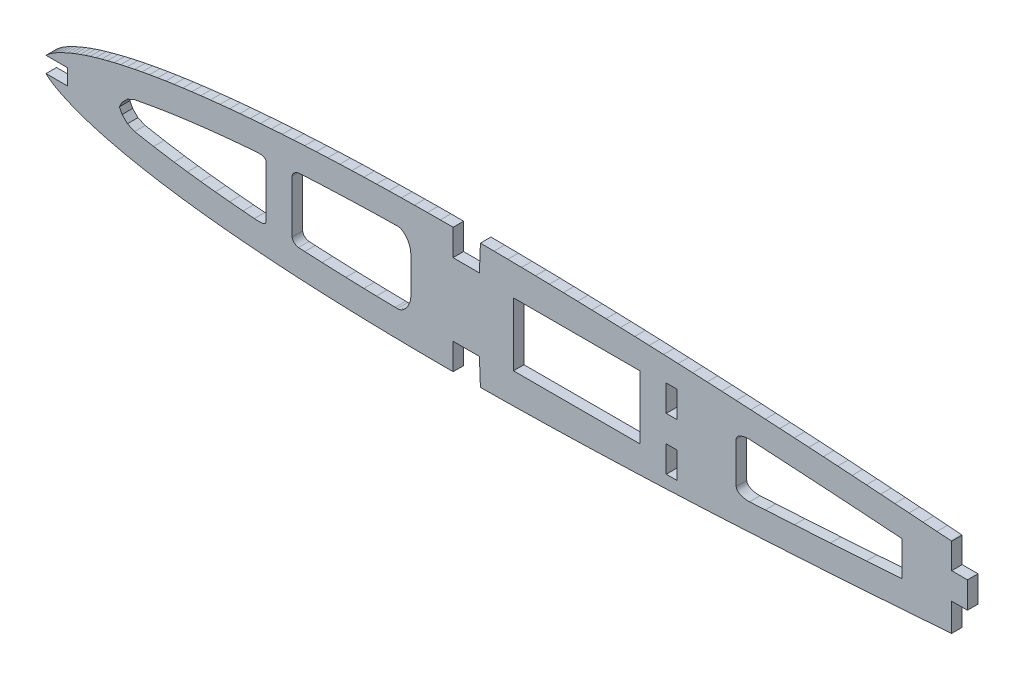
SolidWorks part; units mm, degrees
ref_plane "前视基准面" through (0, 0, 0) normal (0, 0, 1) x (1, 0, 0)
ref_plane "上视基准面" through (0, 0, 0) normal (0, 1, 0) x (1, 0, 0)
ref_plane "右视基准面" through (0, 0, 0) normal (1, 0, 0) x (0, 0, -1)
sketch "Model" plane through (0, 0, 0) normal (0, 0, 1) x (1, 0, 0)
  line L0 (334.1432, -155.4428) -> (338.2569, -155.4428)
  line L1 (338.2569, -155.4428) -> (338.2569, -158.4428)
  line L2 (338.2569, -158.4428) -> (334.1432, -158.4428)
  line L3 (416.4039, -150.0848) -> (416.5959, -145.0858)
  line L4 (416.4039, -150.0848) -> (411.4039, -150.0688)
  line L5 (411.4039, -150.0688) -> (411.4209, -145.0688)
  line L6 (416.4039, -163.8008) -> (416.5959, -168.7998)
  line L7 (416.4039, -163.8008) -> (411.4039, -163.8178)
  line L8 (411.4039, -163.8178) -> (411.4209, -168.8178)
  line L9 (506.0395, -149.3593) -> (505.9039, -149.3488)
  line L10 (505.9039, -149.3488) -> (503.2519, -149.1468)
  line L11 (503.2519, -149.1468) -> (500.5999, -148.9498)
  line L12 (500.5999, -148.9498) -> (497.9479, -148.7548)
  line L13 (497.9479, -148.7548) -> (495.2519, -148.5618)
  line L14 (495.2519, -148.5618) -> (492.5569, -148.3718)
  line L15 (492.5569, -148.3718) -> (489.8609, -148.1858)
  line L16 (489.8609, -148.1858) -> (487.1329, -147.9998)
  line L17 (487.1329, -147.9998) -> (484.4059, -147.8178)
  line L18 (484.4059, -147.8178) -> (481.6779, -147.6418)
  line L19 (481.6779, -147.6418) -> (478.9279, -147.4708)
  line L20 (478.9279, -147.4708) -> (476.1779, -147.3038)
  line L21 (476.1779, -147.3038) -> (473.4269, -147.1408)
  line L22 (473.4269, -147.1408) -> (470.6669, -146.9798)
  line L23 (470.6669, -146.9798) -> (467.9079, -146.8218)
  line L24 (467.9079, -146.8218) -> (465.1469, -146.6688)
  line L25 (465.1469, -146.6688) -> (462.3869, -146.5218)
  line L26 (462.3869, -146.5218) -> (459.6279, -146.3828)
  line L27 (459.6279, -146.3828) -> (456.8669, -146.2488)
  line L28 (456.8669, -146.2488) -> (454.1169, -146.1228)
  line L29 (454.1169, -146.1228) -> (451.3669, -146.0028)
  line L30 (451.3669, -146.0028) -> (448.6159, -145.8878)
  line L31 (448.6159, -145.8878) -> (445.8879, -145.7798)
  line L32 (445.8879, -145.7798) -> (443.1609, -145.6788)
  line L33 (443.1609, -145.6788) -> (440.4329, -145.5848)
  line L34 (440.4329, -145.5848) -> (437.7379, -145.4978)
  line L35 (437.7379, -145.4978) -> (435.0419, -145.4188)
  line L36 (435.0419, -145.4188) -> (432.3459, -145.3468)
  line L37 (432.3459, -145.3468) -> (429.6939, -145.2828)
  line L38 (429.6939, -145.2828) -> (427.0429, -145.2268)
  line L39 (427.0429, -145.2268) -> (424.3899, -145.1788)
  line L40 (424.3899, -145.1788) -> (421.7919, -145.1388)
  line L41 (421.7919, -145.1388) -> (419.1939, -145.1078)
  line L42 (419.1939, -145.1078) -> (416.5959, -145.0858)
  line L43 (350.9749, -154.3268) -> (354.5644, -153.6678)
  line L44 (354.5644, -153.6678) -> (358.4449, -153.0538)
  line L45 (358.4449, -153.0538) -> (360.9819, -152.7033)
  line L46 (360.9819, -152.7033) -> (363.5229, -152.3838)
  line L47 (363.5229, -152.3838) -> (366.2624, -152.0758)
  line L48 (366.2624, -152.0758) -> (369.0039, -151.7948)
  line L49 (369.0039, -151.7948) -> (371.5529, -151.5622)
  line L50 (371.5529, -151.5622) -> (373.8859, -151.3668)
  line L51 (382.21, -150.8083) -> (383.2599, -150.7478)
  line L52 (383.2599, -150.7478) -> (386.5334, -150.5888)
  line L53 (386.5334, -150.5888) -> (386.6385, -150.5846)
  line L54 (386.6385, -150.5846) -> (391.0509, -150.4073)
  line L55 (391.0509, -150.4073) -> (394.4779, -150.2968)
  line L56 (394.4779, -150.2968) -> (396.8539, -150.2348)
  line L57 (396.8539, -150.2348) -> (400.4194, -150.1623)
  line L58 (400.4194, -150.1623) -> (400.8605, -150.1557)
  line L59 (400.8351, -163.7295) -> (400.4194, -163.7233)
  line L60 (400.4194, -163.7233) -> (396.8539, -163.6508)
  line L61 (396.8539, -163.6508) -> (394.4779, -163.5888)
  line L62 (394.4779, -163.5888) -> (391.0509, -163.4783)
  line L63 (391.0509, -163.4783) -> (386.5334, -163.2968)
  line L64 (386.5334, -163.2968) -> (383.2599, -163.1378)
  line L65 (383.2599, -163.1378) -> (382.0634, -163.0689)
  line L66 (373.6903, -162.5024) -> (371.5529, -162.3235)
  line L67 (371.5529, -162.3235) -> (369.0039, -162.0908)
  line L68 (369.0039, -162.0908) -> (366.2624, -161.8098)
  line L69 (366.2624, -161.8098) -> (363.5229, -161.5018)
  line L70 (363.5229, -161.5018) -> (360.9819, -161.1823)
  line L71 (360.9819, -161.1823) -> (358.4449, -160.8318)
  line L72 (358.4449, -160.8318) -> (354.5644, -160.2178)
  line L73 (354.5644, -160.2178) -> (350.9749, -159.5588)
  line L74 (350.9749, -154.3268) -> (349.5928, -154.917)
  line L75 (349.5928, -154.917) -> (348.5947, -155.9412)
  line L76 (348.5947, -155.9412) -> (348.068, -156.9428)
  line L77 (350.9749, -159.5588) -> (349.5928, -158.9686)
  line L78 (349.5928, -158.9686) -> (348.5947, -157.9444)
  line L79 (348.5947, -157.9444) -> (348.068, -156.9428)
  line L80 (467.6693, -151.8109) -> (470.6669, -151.9798)
  line L81 (470.6669, -151.9798) -> (477.1529, -152.3643)
  line L82 (477.1529, -152.3643) -> (483.0419, -152.7298)
  line L83 (483.0419, -152.7298) -> (489.8609, -153.1858)
  line L84 (489.8609, -153.1858) -> (496.5999, -153.6583)
  line L85 (496.5999, -153.6583) -> (496.5999, -160.2273)
  line L86 (496.5999, -160.2273) -> (489.8609, -160.6998)
  line L87 (489.8609, -160.6998) -> (483.0419, -161.1558)
  line L88 (483.0419, -161.1558) -> (476.1779, -161.5818)
  line L89 (476.1779, -161.5818) -> (470.6669, -161.9058)
  line L90 (470.6669, -161.9058) -> (467.6693, -162.0747)
  line L91 (403.377, -153.3609) -> (403.377, -160.5247)
  line L92 (465.1469, -153.0708) -> (465.1469, -160.8149)
  line L93 (380.8691, -151.9428) -> (380.8691, -161.9428)
  line L94 (375.8691, -161.9428) -> (375.8691, -151.9428)
  line L96 (451.8649, -150.4428) -> (453.8649, -150.4428)
  line L97 (453.8649, -150.4428) -> (453.8649, -155.4428)
  line L98 (453.8649, -155.4428) -> (451.8649, -155.4428)
  line L99 (451.8649, -160.4428) -> (453.8649, -160.4428)
  line L100 (453.8649, -160.4428) -> (453.8649, -165.4428)
  line L101 (453.8649, -165.4428) -> (451.8649, -165.4428)
  line L102 (451.8649, -150.4428) -> (451.8649, -155.4428)
  line L103 (451.8649, -160.4428) -> (451.8649, -165.4428)
  line L104 (446.8649, -150.9428) -> (446.8649, -162.9428)
  line L105 (446.8649, -162.9428) -> (422.8649, -162.9428)
  line L106 (422.8649, -162.9428) -> (422.8649, -150.9428)
  line L107 (422.8649, -150.9428) -> (446.8649, -150.9428)
  line L108 (509.0395, -156.7128) -> (509.0395, -159.2128)
  line L109 (509.0395, -156.7128) -> (509.0395, -154.2128)
  line L110 (509.0395, -154.2128) -> (506.0395, -154.2128)
  line L111 (509.0395, -159.2128) -> (506.0395, -159.2128)
  line L112 (506.0395, -154.2128) -> (506.0395, -149.3593)
  line L113 (506.0395, -159.2128) -> (506.0395, -164.5264)
  line L114 (411.4209, -145.0688) -> (408.9909, -145.0728)
  line L115 (408.9909, -145.0728) -> (406.5289, -145.0858)
  line L116 (406.5289, -145.0858) -> (404.0689, -145.1088)
  line L117 (404.0689, -145.1088) -> (401.6079, -145.1418)
  line L118 (401.6079, -145.1418) -> (399.2309, -145.1828)
  line L119 (399.2309, -145.1828) -> (396.8539, -145.2348)
  line L120 (396.8539, -145.2348) -> (394.4779, -145.2968)
  line L121 (394.4779, -145.2968) -> (392.1929, -145.3668)
  line L122 (392.1929, -145.3668) -> (389.9089, -145.4478)
  line L123 (389.9089, -145.4478) -> (387.6249, -145.5398)
  line L124 (387.6249, -145.5398) -> (385.4419, -145.6378)
  line L125 (385.4419, -145.6378) -> (383.2599, -145.7478)
  line L126 (383.2599, -145.7478) -> (381.0779, -145.8698)
  line L127 (381.0779, -145.8698) -> (379.0049, -145.9968)
  line L128 (379.0049, -145.9968) -> (376.9339, -146.1368)
  line L129 (376.9339, -146.1368) -> (374.8629, -146.2888)
  line L130 (374.8629, -146.2888) -> (372.9089, -146.4448)
  line L131 (372.9089, -146.4448) -> (370.9559, -146.6138)
  line L132 (370.9559, -146.6138) -> (369.0039, -146.7948)
  line L133 (369.0039, -146.7948) -> (367.1759, -146.9778)
  line L134 (367.1759, -146.9778) -> (365.3489, -147.1738)
  line L135 (365.3489, -147.1738) -> (363.5229, -147.3838)
  line L136 (363.5229, -147.3838) -> (361.8279, -147.5918)
  line L137 (361.8279, -147.5918) -> (360.1359, -147.8148)
  line L138 (360.1359, -147.8148) -> (358.4449, -148.0538)
  line L139 (358.4449, -148.0538) -> (356.8909, -148.2868)
  line L140 (356.8909, -148.2868) -> (355.3389, -148.5358)
  line L141 (355.3389, -148.5358) -> (353.7899, -148.7998)
  line L142 (353.7899, -148.7998) -> (352.3799, -149.0558)
  line L143 (352.3799, -149.0558) -> (350.9749, -149.3268)
  line L144 (350.9749, -149.3268) -> (349.5719, -149.6148)
  line L145 (349.5719, -149.6148) -> (348.3139, -149.8908)
  line L146 (348.3139, -149.8908) -> (347.0599, -150.1828)
  line L147 (347.0599, -150.1828) -> (345.8099, -150.4938)
  line L148 (345.8099, -150.4938) -> (344.7079, -150.7838)
  line L149 (344.7079, -150.7838) -> (343.6099, -151.0918)
  line L150 (343.6099, -151.0918) -> (342.5179, -151.4198)
  line L151 (342.5179, -151.4198) -> (341.5759, -151.7218)
  line L152 (341.5759, -151.7218) -> (340.6399, -152.0448)
  line L153 (340.6399, -152.0448) -> (339.7119, -152.3898)
  line L154 (339.7119, -152.3898) -> (338.9339, -152.7018)
  line L155 (338.9339, -152.7018) -> (338.1629, -153.0328)
  line L156 (338.1629, -153.0328) -> (337.4009, -153.3818)
  line L157 (337.4009, -153.3818) -> (336.7869, -153.6818)
  line L158 (336.7869, -153.6818) -> (336.1839, -154.0018)
  line L159 (336.1839, -154.0018) -> (335.5939, -154.3478)
  line L160 (335.5939, -154.3478) -> (335.1439, -154.6418)
  line L161 (335.1439, -154.6418) -> (334.7099, -154.9578)
  line L162 (334.7099, -154.9578) -> (334.2959, -155.2998)
  line L163 (334.2959, -155.2998) -> (334.1432, -155.4428)
  line L164 (416.5959, -168.7998) -> (419.1939, -168.7778)
  line L165 (419.1939, -168.7778) -> (421.7919, -168.7468)
  line L166 (421.7919, -168.7468) -> (424.3899, -168.7078)
  line L167 (424.3899, -168.7078) -> (427.0429, -168.6588)
  line L168 (427.0429, -168.6588) -> (429.6939, -168.6028)
  line L169 (429.6939, -168.6028) -> (432.3459, -168.5388)
  line L170 (432.3459, -168.5388) -> (435.0419, -168.4668)
  line L171 (435.0419, -168.4668) -> (437.7379, -168.3878)
  line L172 (437.7379, -168.3878) -> (440.4329, -168.3008)
  line L173 (440.4329, -168.3008) -> (443.1609, -168.2068)
  line L174 (443.1609, -168.2068) -> (445.8879, -168.1058)
  line L175 (445.8879, -168.1058) -> (448.6159, -167.9978)
  line L176 (448.6159, -167.9978) -> (451.3669, -167.8838)
  line L177 (451.3669, -167.8838) -> (454.1169, -167.7628)
  line L178 (454.1169, -167.7628) -> (456.8669, -167.6368)
  line L179 (456.8669, -167.6368) -> (459.6279, -167.5028)
  line L180 (459.6279, -167.5028) -> (462.3869, -167.3638)
  line L181 (462.3869, -167.3638) -> (465.1469, -167.2168)
  line L182 (465.1469, -167.2168) -> (467.9079, -167.0638)
  line L183 (467.9079, -167.0638) -> (470.6669, -166.9068)
  line L184 (470.6669, -166.9068) -> (473.4269, -166.7448)
  line L185 (473.4269, -166.7448) -> (476.1779, -166.5818)
  line L186 (476.1779, -166.5818) -> (478.9279, -166.4158)
  line L187 (478.9279, -166.4158) -> (481.6779, -166.2438)
  line L188 (481.6779, -166.2438) -> (484.4059, -166.0678)
  line L189 (484.4059, -166.0678) -> (487.1329, -165.8858)
  line L190 (487.1329, -165.8858) -> (489.8609, -165.7008)
  line L191 (489.8609, -165.7008) -> (492.5569, -165.5138)
  line L192 (492.5569, -165.5138) -> (495.2519, -165.3238)
  line L193 (495.2519, -165.3238) -> (497.9479, -165.1308)
  line L194 (497.9479, -165.1308) -> (500.5999, -164.9368)
  line L195 (500.5999, -164.9368) -> (503.2519, -164.7388)
  line L196 (503.2519, -164.7388) -> (505.9039, -164.5368)
  line L197 (505.9039, -164.5368) -> (506.0395, -164.5264)
  line L198 (334.1432, -158.4428) -> (334.2959, -158.5858)
  line L199 (334.2959, -158.5858) -> (334.7099, -158.9278)
  line L200 (334.7099, -158.9278) -> (335.1439, -159.2438)
  line L201 (335.1439, -159.2438) -> (335.5939, -159.5388)
  line L202 (335.5939, -159.5388) -> (336.1839, -159.8848)
  line L203 (336.1839, -159.8848) -> (336.7869, -160.2038)
  line L204 (336.7869, -160.2038) -> (337.4009, -160.5038)
  line L205 (337.4009, -160.5038) -> (338.1629, -160.8538)
  line L206 (338.1629, -160.8538) -> (338.9339, -161.1838)
  line L207 (338.9339, -161.1838) -> (339.7119, -161.4958)
  line L208 (339.7119, -161.4958) -> (340.6399, -161.8408)
  line L209 (340.6399, -161.8408) -> (341.5759, -162.1638)
  line L210 (341.5759, -162.1638) -> (342.5179, -162.4668)
  line L211 (342.5179, -162.4668) -> (343.6099, -162.7938)
  line L212 (343.6099, -162.7938) -> (344.7079, -163.1018)
  line L213 (344.7079, -163.1018) -> (345.8099, -163.3928)
  line L214 (345.8099, -163.3928) -> (347.0599, -163.7028)
  line L215 (347.0599, -163.7028) -> (348.3139, -163.9948)
  line L216 (348.3139, -163.9948) -> (349.5719, -164.2708)
  line L217 (349.5719, -164.2708) -> (350.9749, -164.5598)
  line L218 (350.9749, -164.5598) -> (352.3799, -164.8308)
  line L219 (352.3799, -164.8308) -> (353.7899, -165.0858)
  line L220 (353.7899, -165.0858) -> (355.3389, -165.3498)
  line L221 (355.3389, -165.3498) -> (356.8909, -165.5988)
  line L222 (356.8909, -165.5988) -> (358.4449, -165.8318)
  line L223 (358.4449, -165.8318) -> (360.1359, -166.0708)
  line L224 (360.1359, -166.0708) -> (361.8279, -166.2938)
  line L225 (361.8279, -166.2938) -> (363.5229, -166.5018)
  line L226 (363.5229, -166.5018) -> (365.3489, -166.7118)
  line L227 (365.3489, -166.7118) -> (367.1759, -166.9078)
  line L228 (367.1759, -166.9078) -> (369.0039, -167.0908)
  line L229 (369.0039, -167.0908) -> (370.9559, -167.2718)
  line L230 (370.9559, -167.2718) -> (372.9089, -167.4408)
  line L231 (372.9089, -167.4408) -> (374.8629, -167.5968)
  line L232 (374.8629, -167.5968) -> (376.9339, -167.7498)
  line L233 (376.9339, -167.7498) -> (379.0049, -167.8888)
  line L234 (379.0049, -167.8888) -> (381.0779, -168.0168)
  line L235 (381.0779, -168.0168) -> (383.2599, -168.1378)
  line L236 (383.2599, -168.1378) -> (385.4419, -168.2478)
  line L237 (385.4419, -168.2478) -> (387.6249, -168.3458)
  line L238 (387.6249, -168.3458) -> (389.9089, -168.4378)
  line L239 (389.9089, -168.4378) -> (392.1929, -168.5188)
  line L240 (392.1929, -168.5188) -> (394.4779, -168.5888)
  line L241 (394.4779, -168.5888) -> (396.8539, -168.6508)
  line L242 (396.8539, -168.6508) -> (399.2309, -168.7028)
  line L243 (399.2309, -168.7028) -> (401.6079, -168.7448)
  line L244 (401.6079, -168.7448) -> (404.0689, -168.7768)
  line L245 (404.0689, -168.7768) -> (406.5289, -168.7998)
  line L246 (406.5289, -168.7998) -> (408.9909, -168.8128)
  line L247 (408.9909, -168.8128) -> (411.4209, -168.8178)
  spline S0 degree 3 poles (400.8605, -150.1557) (402.2187, -150.1354) (403.377, -152.0025) (403.377, -153.3609) knots 0 0 0 0 4.075049 4.075049 4.075049 4.075049
  spline S1 degree 3 poles (400.8351, -163.7295) (402.1985, -163.7499) (403.377, -161.8882) (403.377, -160.5247) knots 0 0 0 0 4.090494 4.090494 4.090494 4.090494
  spline S2 degree 3 poles (465.1469, -153.0708) (465.1469, -152.1309) (466.7309, -151.7581) (467.6693, -151.8109) knots 0 0 0 0 2.819498 2.819498 2.819498 2.819498
  spline S3 degree 3 poles (465.1469, -160.8149) (465.1469, -161.7548) (466.7309, -162.1276) (467.6693, -162.0747) knots 0 0 0 0 2.819482 2.819482 2.819482 2.819482
  spline S4 degree 3 poles (373.8859, -151.3668) (374.5719, -151.3094) (375.8691, -151.2544) (375.8691, -151.9428) knots 0 0 0 0 2.065193 2.065193 2.065193 2.065193
  spline S5 degree 3 poles (373.6903, -162.5024) (374.4375, -162.565) (375.8691, -162.6927) (375.8691, -161.9428) knots 0 0 0 0 2.249548 2.249548 2.249548 2.249548
  spline S6 degree 3 poles (382.21, -150.8083) (381.6255, -150.842) (380.8691, -151.3574) (380.8691, -151.9428) knots 0 0 0 0 1.756378 1.756378 1.756378 1.756378
  spline S7 degree 3 poles (382.0634, -163.0689) (381.5171, -163.0374) (380.8691, -162.49) (380.8691, -161.9428) knots 0 0 0 0 1.641388 1.641388 1.641388 1.641388
extrude "凸台-拉伸1" add sketch "Model" along normal blind 2
